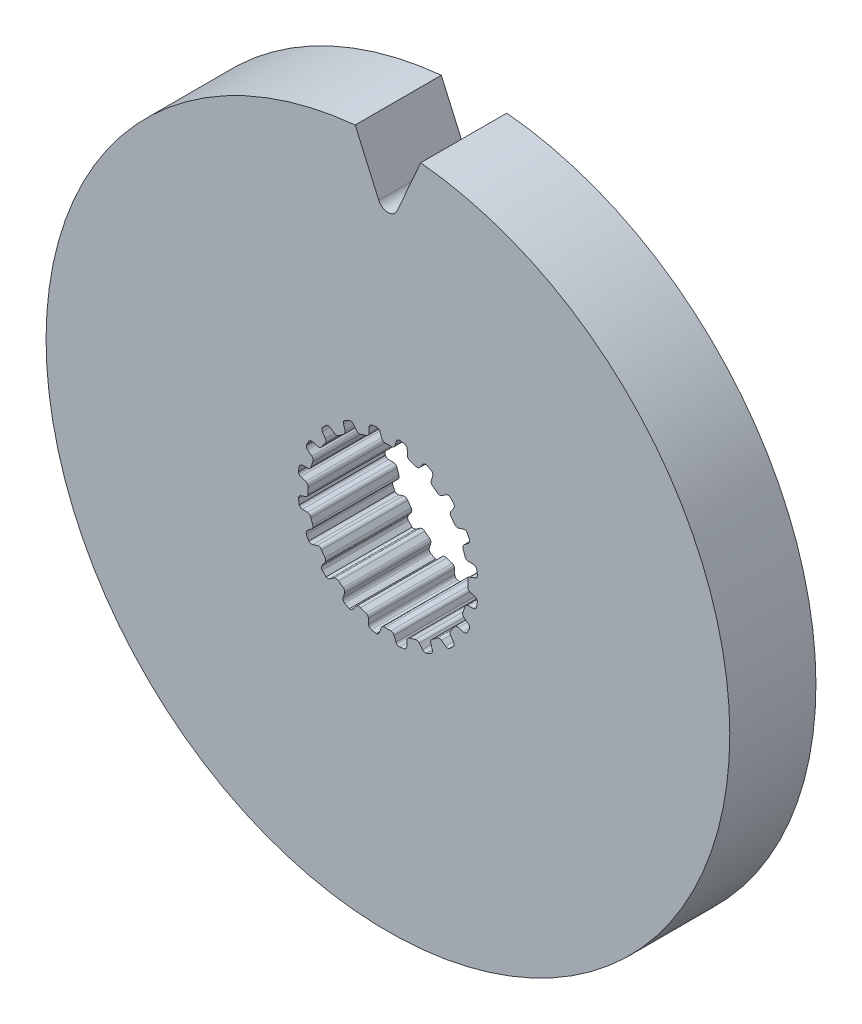
SolidWorks part; units mm, degrees
ref_plane "Front Plane" through (0, 0, 0) normal (0, 0, 1) x (1, 0, 0)
ref_plane "Top Plane" through (0, 0, 0) normal (0, 1, 0) x (1, 0, 0)
ref_plane "Right Plane" through (0, 0, 0) normal (1, 0, 0) x (0, 0, -1)
sketch "Sketch1" plane through (0, 0, 0) normal (0, 0, 1) x (1, 0, 0)
  line L0 (-0.1069, 2.9699) -> (0.1069, 2.9699)
  line L1 (0.3159, 3.2375) -> (0.2537, 3.0575)
  line L2 (-0.2964, 3.2367) -> (-0.2318, 3.0575)
  line L3 (-0.2964, 3.2367) -> (0.3159, 3.2375) construction
  line L4 (0, 3.3252) -> (0, 0) construction
  line L5 (-0.2318, 3.0575) -> (0.2537, 3.0575) construction
  line L6 (-0.4281, 3.3241) -> (0.4281, 3.3263) construction
  line L7 (0.7183, 3.1698) -> (0.7244, 2.9795)
  line L8 (0.816, 2.8576) -> (1.0195, 2.7915)
  line L9 (1.3009, 2.9815) -> (1.1862, 2.8295)
  line L10 (1.6627, 2.7927) -> (1.6097, 2.6099)
  line L11 (1.6591, 2.4655) -> (1.8322, 2.3398)
  line L12 (2.1585, 2.4335) -> (2.0025, 2.3245)
  line L13 (2.4443, 2.1423) -> (2.3374, 1.9847)
  line L14 (2.3398, 1.8322) -> (2.4655, 1.6591)
  line L15 (2.8049, 1.6474) -> (2.6228, 1.5919)
  line L16 (2.9866, 1.2821) -> (2.8363, 1.1653)
  line L17 (2.7915, 1.0195) -> (2.8576, 0.816)
  line L18 (3.1767, 0.7) -> (2.9863, 0.7035)
  line L19 (3.2367, 0.2964) -> (3.0575, 0.2318)
  line L20 (2.9699, 0.1069) -> (2.9699, -0.1069)
  line L21 (3.2375, -0.3159) -> (3.0575, -0.2537)
  line L22 (3.1698, -0.7183) -> (2.9795, -0.7244)
  line L23 (2.8576, -0.816) -> (2.7915, -1.0195)
  line L24 (2.9815, -1.3009) -> (2.8295, -1.1862)
  line L25 (2.7927, -1.6627) -> (2.6099, -1.6097)
  line L26 (2.4655, -1.6591) -> (2.3398, -1.8322)
  line L27 (2.4335, -2.1585) -> (2.3245, -2.0025)
  line L28 (2.1423, -2.4443) -> (1.9847, -2.3374)
  line L29 (1.8322, -2.3398) -> (1.6591, -2.4655)
  line L30 (1.6474, -2.8049) -> (1.5919, -2.6228)
  line L31 (1.2821, -2.9866) -> (1.1653, -2.8363)
  line L32 (1.0195, -2.7915) -> (0.816, -2.8576)
  line L33 (0.7, -3.1767) -> (0.7035, -2.9863)
  line L34 (0.2964, -3.2367) -> (0.2318, -3.0575)
  line L35 (0.1069, -2.9699) -> (-0.1069, -2.9699)
  line L36 (-0.3159, -3.2375) -> (-0.2537, -3.0575)
  line L37 (-0.7183, -3.1698) -> (-0.7244, -2.9795)
  line L38 (-0.816, -2.8576) -> (-1.0195, -2.7915)
  line L39 (-1.3009, -2.9815) -> (-1.1862, -2.8295)
  line L40 (-1.6627, -2.7927) -> (-1.6097, -2.6099)
  line L41 (-1.6591, -2.4655) -> (-1.8322, -2.3398)
  line L42 (-2.1585, -2.4335) -> (-2.0025, -2.3245)
  line L43 (-2.4443, -2.1423) -> (-2.3374, -1.9847)
  line L44 (-2.3398, -1.8322) -> (-2.4655, -1.6591)
  line L45 (-2.8049, -1.6474) -> (-2.6228, -1.5919)
  line L46 (-2.9866, -1.2821) -> (-2.8363, -1.1653)
  line L47 (-2.7915, -1.0195) -> (-2.8576, -0.816)
  line L48 (-3.1767, -0.7) -> (-2.9863, -0.7035)
  line L49 (-3.2367, -0.2964) -> (-3.0575, -0.2318)
  line L50 (-2.9699, -0.1069) -> (-2.9699, 0.1069)
  line L51 (-3.2375, 0.3159) -> (-3.0575, 0.2537)
  line L52 (-3.1698, 0.7183) -> (-2.9795, 0.7244)
  line L53 (-2.8576, 0.816) -> (-2.7915, 1.0195)
  line L54 (-2.9815, 1.3009) -> (-2.8295, 1.1862)
  line L55 (-2.7927, 1.6627) -> (-2.6099, 1.6097)
  line L56 (-2.4655, 1.6591) -> (-2.3398, 1.8322)
  line L57 (-2.4335, 2.1585) -> (-2.3245, 2.0025)
  line L58 (-2.1423, 2.4443) -> (-1.9847, 2.3374)
  line L59 (-1.8322, 2.3398) -> (-1.6591, 2.4655)
  line L60 (-1.6474, 2.8049) -> (-1.5919, 2.6228)
  line L61 (-1.2821, 2.9866) -> (-1.1653, 2.8363)
  line L62 (-1.0195, 2.7915) -> (-0.816, 2.8576)
  line L63 (-0.7, 3.1767) -> (-0.7035, 2.9863)
  line L64 (0.4281, 3.3263) -> (0.62, 3.2938)
  line L65 (1.4351, 3.0312) -> (1.6075, 2.9409)
  line L66 (2.3015, 2.4394) -> (2.4376, 2.3003)
  line L67 (2.9427, 1.6088) -> (3.0291, 1.4344)
  line L68 (3.2958, 0.6207) -> (3.3241, 0.4281)
  line L69 (3.3263, -0.4281) -> (3.2938, -0.62)
  line L70 (3.0312, -1.4351) -> (2.9409, -1.6075)
  line L71 (2.4394, -2.3015) -> (2.3003, -2.4376)
  line L72 (1.6088, -2.9427) -> (1.4344, -3.0291)
  line L73 (0.6207, -3.2958) -> (0.4281, -3.3241)
  line L74 (-0.4281, -3.3263) -> (-0.62, -3.2938)
  line L75 (-1.4351, -3.0312) -> (-1.6075, -2.9409)
  line L76 (-2.3015, -2.4394) -> (-2.4376, -2.3003)
  line L77 (-2.9427, -1.6088) -> (-3.0291, -1.4344)
  line L78 (-3.2958, -0.6207) -> (-3.3241, -0.4281)
  line L79 (-3.3263, 0.4281) -> (-3.2938, 0.62)
  line L80 (-3.0312, 1.4351) -> (-2.9409, 1.6075)
  line L81 (-2.4394, 2.3015) -> (-2.3003, 2.4376)
  line L82 (-1.6088, 2.9427) -> (-1.4344, 3.0291)
  line L83 (-0.6207, 3.2958) -> (-0.4281, 3.3241)
  arc A0 (0.2537, 3.0575) -> (0.1069, 2.9699) centre (0.1283, 3.1009) cw
  arc A1 (-0.2318, 3.0575) -> (-0.1069, 2.9699) centre (-0.1069, 3.1026) ccw
  arc A2 (0.62, 3.2938) -> (0.7183, 3.1698) centre (0.5856, 3.1656) cw
  arc A3 (0.7244, 2.9795) -> (0.816, 2.8576) centre (0.857, 2.9838) ccw
  arc A4 (-0.4281, 3.3241) -> (-0.2964, 3.2367) centre (-0.4213, 3.1916) cw
  arc A5 (0.4281, 3.3263) -> (0.3159, 3.2375) centre (0.4413, 3.1942) ccw
  arc A6 (1.1862, 2.8295) -> (1.0195, 2.7915) centre (1.0802, 2.9095) cw
  arc A7 (1.4351, 3.0312) -> (1.3009, 2.9815) centre (1.4068, 2.9015) ccw
  arc A8 (1.6075, 2.9409) -> (1.6627, 2.7927) centre (1.5352, 2.8297) cw
  arc A9 (1.6097, 2.6099) -> (1.6591, 2.4655) centre (1.7371, 2.5729) ccw
  arc A10 (2.0025, 2.3245) -> (1.8322, 2.3398) centre (1.9264, 2.4332) cw
  arc A11 (2.3015, 2.4394) -> (2.1585, 2.4335) centre (2.2346, 2.3248) ccw
  arc A12 (2.4376, 2.3003) -> (2.4443, 2.1423) centre (2.3345, 2.2168) cw
  arc A13 (2.3374, 1.9847) -> (2.3398, 1.8322) centre (2.4472, 1.9102) ccw
  arc A14 (2.6228, 1.5919) -> (2.4655, 1.6591) centre (2.5841, 1.7189) cw
  arc A15 (2.9427, 1.6088) -> (2.8049, 1.6474) centre (2.8436, 1.5205) ccw
  arc A16 (3.0291, 1.4344) -> (2.9866, 1.2821) centre (2.9052, 1.3869) cw
  arc A17 (2.8363, 1.1653) -> (2.7915, 1.0195) centre (2.9177, 1.0605) ccw
  arc A18 (2.9863, 0.7035) -> (2.8576, 0.816) centre (2.9887, 0.8362) cw
  arc A19 (3.2958, 0.6207) -> (3.1767, 0.7) centre (3.1743, 0.5673) ccw
  arc A20 (3.3241, 0.4281) -> (3.2367, 0.2964) centre (3.1916, 0.4213) cw
  arc A21 (3.0575, 0.2318) -> (2.9699, 0.1069) centre (3.1026, 0.1069) ccw
  arc A22 (3.0575, -0.2537) -> (2.9699, -0.1069) centre (3.1009, -0.1283) cw
  arc A23 (3.3263, -0.4281) -> (3.2375, -0.3159) centre (3.1942, -0.4413) ccw
  arc A24 (3.2938, -0.62) -> (3.1698, -0.7183) centre (3.1656, -0.5856) cw
  arc A25 (2.9795, -0.7244) -> (2.8576, -0.816) centre (2.9838, -0.857) ccw
  arc A26 (2.8295, -1.1862) -> (2.7915, -1.0195) centre (2.9095, -1.0802) cw
  arc A27 (3.0312, -1.4351) -> (2.9815, -1.3009) centre (2.9015, -1.4068) ccw
  arc A28 (2.9409, -1.6075) -> (2.7927, -1.6627) centre (2.8297, -1.5352) cw
  arc A29 (2.6099, -1.6097) -> (2.4655, -1.6591) centre (2.5729, -1.7371) ccw
  arc A30 (2.3245, -2.0025) -> (2.3398, -1.8322) centre (2.4332, -1.9264) cw
  arc A31 (2.4394, -2.3015) -> (2.4335, -2.1585) centre (2.3248, -2.2346) ccw
  arc A32 (2.3003, -2.4376) -> (2.1423, -2.4443) centre (2.2168, -2.3345) cw
  arc A33 (1.9847, -2.3374) -> (1.8322, -2.3398) centre (1.9102, -2.4472) ccw
  arc A34 (1.5919, -2.6228) -> (1.6591, -2.4655) centre (1.7189, -2.5841) cw
  arc A35 (1.6088, -2.9427) -> (1.6474, -2.8049) centre (1.5205, -2.8436) ccw
  arc A36 (1.4344, -3.0291) -> (1.2821, -2.9866) centre (1.3869, -2.9052) cw
  arc A37 (1.1653, -2.8363) -> (1.0195, -2.7915) centre (1.0605, -2.9177) ccw
  arc A38 (0.7035, -2.9863) -> (0.816, -2.8576) centre (0.8362, -2.9887) cw
  arc A39 (0.6207, -3.2958) -> (0.7, -3.1767) centre (0.5673, -3.1743) ccw
  arc A40 (0.4281, -3.3241) -> (0.2964, -3.2367) centre (0.4213, -3.1916) cw
  arc A41 (0.2318, -3.0575) -> (0.1069, -2.9699) centre (0.1069, -3.1026) ccw
  arc A42 (-0.2537, -3.0575) -> (-0.1069, -2.9699) centre (-0.1283, -3.1009) cw
  arc A43 (-0.4281, -3.3263) -> (-0.3159, -3.2375) centre (-0.4413, -3.1942) ccw
  arc A44 (-0.62, -3.2938) -> (-0.7183, -3.1698) centre (-0.5856, -3.1656) cw
  arc A45 (-0.7244, -2.9795) -> (-0.816, -2.8576) centre (-0.857, -2.9838) ccw
  arc A46 (-1.1862, -2.8295) -> (-1.0195, -2.7915) centre (-1.0802, -2.9095) cw
  arc A47 (-1.4351, -3.0312) -> (-1.3009, -2.9815) centre (-1.4068, -2.9015) ccw
  arc A48 (-1.6075, -2.9409) -> (-1.6627, -2.7927) centre (-1.5352, -2.8297) cw
  arc A49 (-1.6097, -2.6099) -> (-1.6591, -2.4655) centre (-1.7371, -2.5729) ccw
  arc A50 (-2.0025, -2.3245) -> (-1.8322, -2.3398) centre (-1.9264, -2.4332) cw
  arc A51 (-2.3015, -2.4394) -> (-2.1585, -2.4335) centre (-2.2346, -2.3248) ccw
  arc A52 (-2.4376, -2.3003) -> (-2.4443, -2.1423) centre (-2.3345, -2.2168) cw
  arc A53 (-2.3374, -1.9847) -> (-2.3398, -1.8322) centre (-2.4472, -1.9102) ccw
  arc A54 (-2.6228, -1.5919) -> (-2.4655, -1.6591) centre (-2.5841, -1.7189) cw
  arc A55 (-2.9427, -1.6088) -> (-2.8049, -1.6474) centre (-2.8436, -1.5205) ccw
  arc A56 (-3.0291, -1.4344) -> (-2.9866, -1.2821) centre (-2.9052, -1.3869) cw
  arc A57 (-2.8363, -1.1653) -> (-2.7915, -1.0195) centre (-2.9177, -1.0605) ccw
  arc A58 (-2.9863, -0.7035) -> (-2.8576, -0.816) centre (-2.9887, -0.8362) cw
  arc A59 (-3.2958, -0.6207) -> (-3.1767, -0.7) centre (-3.1743, -0.5673) ccw
  arc A60 (-3.3241, -0.4281) -> (-3.2367, -0.2964) centre (-3.1916, -0.4213) cw
  arc A61 (-3.0575, -0.2318) -> (-2.9699, -0.1069) centre (-3.1026, -0.1069) ccw
  arc A62 (-3.0575, 0.2537) -> (-2.9699, 0.1069) centre (-3.1009, 0.1283) cw
  arc A63 (-3.3263, 0.4281) -> (-3.2375, 0.3159) centre (-3.1942, 0.4413) ccw
  arc A64 (-3.2938, 0.62) -> (-3.1698, 0.7183) centre (-3.1656, 0.5856) cw
  arc A65 (-2.9795, 0.7244) -> (-2.8576, 0.816) centre (-2.9838, 0.857) ccw
  arc A66 (-2.8295, 1.1862) -> (-2.7915, 1.0195) centre (-2.9095, 1.0802) cw
  arc A67 (-3.0312, 1.4351) -> (-2.9815, 1.3009) centre (-2.9015, 1.4068) ccw
  arc A68 (-2.9409, 1.6075) -> (-2.7927, 1.6627) centre (-2.8297, 1.5352) cw
  arc A69 (-2.6099, 1.6097) -> (-2.4655, 1.6591) centre (-2.5729, 1.7371) ccw
  arc A70 (-2.3245, 2.0025) -> (-2.3398, 1.8322) centre (-2.4332, 1.9264) cw
  arc A71 (-2.4394, 2.3015) -> (-2.4335, 2.1585) centre (-2.3248, 2.2346) ccw
  arc A72 (-2.3003, 2.4376) -> (-2.1423, 2.4443) centre (-2.2168, 2.3345) cw
  arc A73 (-1.9847, 2.3374) -> (-1.8322, 2.3398) centre (-1.9102, 2.4472) ccw
  arc A74 (-1.5919, 2.6228) -> (-1.6591, 2.4655) centre (-1.7189, 2.5841) cw
  arc A75 (-1.6088, 2.9427) -> (-1.6474, 2.8049) centre (-1.5205, 2.8436) ccw
  arc A76 (-1.4344, 3.0291) -> (-1.2821, 2.9866) centre (-1.3869, 2.9052) cw
  arc A77 (-1.1653, 2.8363) -> (-1.0195, 2.7915) centre (-1.0605, 2.9177) ccw
  arc A78 (-0.7035, 2.9863) -> (-0.816, 2.8576) centre (-0.8362, 2.9887) cw
  arc A79 (-0.6207, 3.2958) -> (-0.7, 3.1767) centre (-0.5673, 3.1743) ccw
  circle A80 centre (0, 0) radius 12.7
  point P14 (0, 2.9699)
  point P247 (0, 0)
  dimension "D4" = 0.1327
  dimension "D8" = 20
  dimension "D9" = 25.4
  dimension "D1" = 2.9699
  dimension "D2" = 0.2139
  dimension "D3" = 0.1904
  dimension "D5" = 0.0877
  dimension "D6" = 0.4855
  dimension "D7" = 0.8563
extrude "Boss-Extrude1" add sketch "Sketch1" along normal mid plane 3.2004
sketch "Sketch2" plane through (0, 0, 1.6002) normal (0, 0, 1) x (1, 0, 0)
  line L0 (0, 12.6416) -> (0, 0) construction
  line L1 (1.557, 23.2996) -> (0, 0) construction
  line L2 (-1.2164, 12.6416) -> (1.2164, 12.6416) construction
  line L3 (-0.7785, 11.6498) -> (0.7785, 11.6498) construction
  line L4 (-1.2164, 12.6416) -> (-0.3406, 10.658)
  line L5 (1.2164, 12.6416) -> (0.3406, 10.658)
  circle A0 centre (0, 0) radius 12.7 construction
  arc A1 (-0.3406, 10.658) -> (0.3406, 10.658) centre (0, 10.8084) ccw
  arc A2 (-1.2164, 12.6416) -> (1.2164, 12.6416) centre (0, 0) cw
  point P9 (0, 11.6498)
  point P10 (-3.3328, 17.4905)
  point P15 (-3.8137, 22.3657)
  point P16 (-2.5168, 19.7102)
  point P17 (-0.338, 20.6722)
  point P18 (0.8699, 27.1033)
  dimension "D1" = 0.9918
  dimension "D2" = 1.557
  dimension "D3" = 20
extrude "Cut-Extrude1" cut sketch "Sketch2" against normal up to surface (3.2004 mm away) up to face at (12.7, 0, -1.6002)
